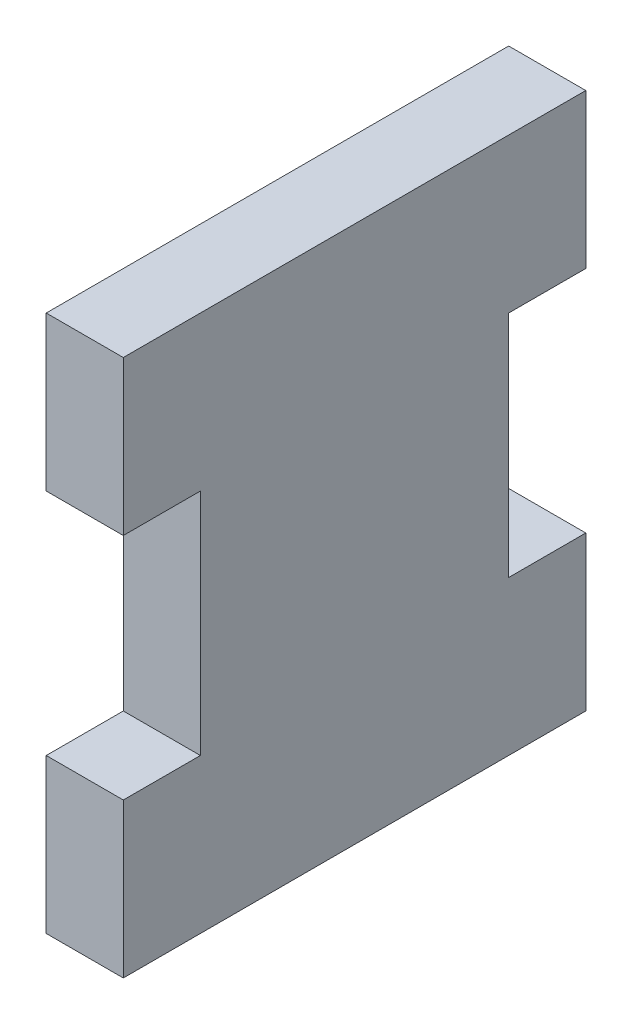
SolidWorks part; units mm, degrees
ref_plane "Front Plane" through (0, 0, 0) normal (0, 0, 1) x (1, 0, 0)
ref_plane "Top Plane" through (0, 0, 0) normal (0, 1, 0) x (1, 0, 0)
ref_plane "Right Plane" through (0, 0, 0) normal (1, 0, 0) x (0, 0, -1)
sketch "Sketch1" plane through (0, 0, 0) normal (0, 0, 1) x (1, 0, 0)
  line L1 (135.126, 74.4185) -> (131.951, 74.4185)
  line L2 (135.126, 74.4185) -> (135.126, 96.5527)
  line L3 (135.126, 96.5527) -> (131.951, 96.5527)
  line L4 (131.951, 74.4185) -> (131.951, 96.5527)
  dimension "D1" = 3.175
extrude "Boss-Extrude1" add sketch "Sketch1" against normal up to surface (19.05 mm away) contours L2 L3 L4 L1
sketch "Sketch2" plane through (135.126, 0, 0) normal (1, 0, 0) x (0, 0, -1)
  line L0 (0, 74.4185) -> (0, 96.5527) construction
  line L1 (0, 90.2027) -> (3.175, 90.2027)
  line L2 (0, 90.2027) -> (0, 80.7685)
  line L3 (0, 80.7685) -> (3.175, 80.7685)
  line L4 (3.175, 90.2027) -> (3.175, 80.7685)
  line L5 (3.175, 70.9591) -> (3.175, 111.0627) construction
  line L6 (15.875, 111.0627) -> (15.875, 70.9591) construction
  line L7 (15.875, 80.7685) -> (19.05, 80.7685)
  line L8 (15.875, 80.7685) -> (15.875, 90.2027)
  line L9 (15.875, 90.2027) -> (19.05, 90.2027)
  line L10 (19.05, 80.7685) -> (19.05, 90.2027)
  line L11 (19.05, 96.5527) -> (19.05, 74.4185) construction
  line L12 (19.05, 96.5527) -> (0, 96.5527) construction
  line L13 (19.05, 74.4185) -> (0, 74.4185) construction
  dimension "D1" = 6.35
  dimension "D2" = 6.35
  dimension "D3" = 6.35
  dimension "D4" = 6.35
extrude "Cut-Extrude1" cut sketch "Sketch2" against normal blind 5.08
